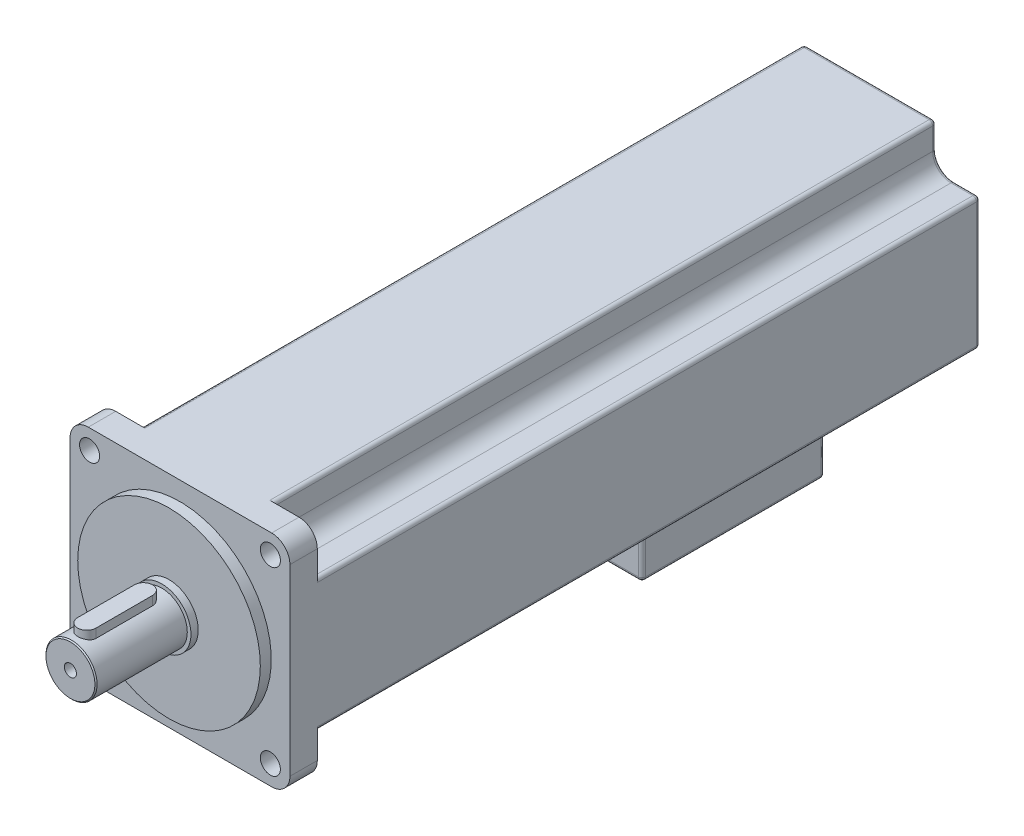
SolidWorks part; units mm, degrees
ref_plane "前视基准面" through (0, 0, 0) normal (0, 0, 1) x (1, 0, 0)
ref_plane "上视基准面" through (0, 0, 0) normal (0, 1, 0) x (1, 0, 0)
ref_plane "右视基准面" through (0, 0, 0) normal (1, 0, 0) x (0, 0, -1)
sketch "草图1" plane through (0, 0, 0) normal (0, 0, 1) x (1, 0, 0)
  line L1 (-30.1, -30.1) -> (30.1, -30.1)
  line L2 (-30.1, -30.1) -> (-30.1, 30.1)
  line L3 (-30.1, 30.1) -> (30.1, 30.1)
  line L4 (30.1, -30.1) -> (30.1, 30.1)
  line L5 (-30.1, -30.1) -> (30.1, 30.1) construction
  line L6 (-30.1, 30.1) -> (30.1, -30.1) construction
  point P0 (0, 0)
  dimension "D1" = 60.2
  dimension "D2" = 60.2
extrude "凸台-拉伸1" add sketch "草图1" along normal blind 7.5
fillet "圆角1" radius 5 4 edges at (-30.1, -30.1, 3.75) (30.1, -30.1, 3.75) (30.1, 30.1, 3.75) (-30.1, 30.1, 3.75)
sketch "草图2" plane through (0, 0, 7.5) normal (0, 0, 1) x (1, 0, 0)
  line L1 (-24.7487, 24.7487) -> (24.7487, 24.7487) construction
  line L2 (-24.7487, 24.7487) -> (-24.7487, -24.7487) construction
  line L3 (-24.7487, -24.7487) -> (24.7487, -24.7487) construction
  line L4 (24.7487, 24.7487) -> (24.7487, -24.7487) construction
  line L5 (-24.7487, 24.7487) -> (24.7487, -24.7487) construction
  line L6 (-24.7487, -24.7487) -> (24.7487, 24.7487) construction
  circle A0 centre (0, 0) radius 35 construction
  circle A1 centre (-24.7487, 24.7487) radius 2.75
  circle A2 centre (24.7487, 24.7487) radius 2.75
  circle A3 centre (24.7487, -24.7487) radius 2.75
  circle A4 centre (-24.7487, -24.7487) radius 2.75
  dimension "D1" = 70
  dimension "D2" = 5.5
extrude "切除-拉伸1" cut sketch "草图2" against normal through all
sketch "草图3" plane through (0, 0, 7.5) normal (0, 0, 1) x (1, 0, 0)
  circle A0 centre (0, 0) radius 25
  dimension "D1" = 50
extrude "凸台-拉伸2" add sketch "草图3" along normal blind 3
sketch "草图4" plane through (0, 0, 10.5) normal (0, 0, 1) x (1, 0, 0)
  circle A0 centre (0, 0) radius 8
  dimension "D1" = 16
extrude "凸台-拉伸3" add sketch "草图4" along normal blind 2
sketch "草图5" plane through (0, 0, 12.5) normal (0, 0, 1) x (1, 0, 0)
  circle A0 centre (0, 0) radius 7
  dimension "D1" = 14
extrude "凸台-拉伸4" add sketch "草图5" along normal blind 25
hole_wizard "M4 螺纹孔2" positions "草图8" profile "草图9" tap size "M4" standard "ISO"
sketch "草图8" plane through (0, 0, 37.5) normal (0, 0, 1) x (1, 0, 0)
  point P0 (0, 0)
sketch "草图9" plane through (0, 0, 37.5) normal (1, 0, 0) x (0, -1, 0)
  line L0 (0, 0) -> (0, 11.0914)
  line L1 (0, 11.0914) -> (1.65, 10.1)
  line L2 (1.65, 10.1) -> (1.65, 0)
  line L5 (1.65, 0) -> (0, 0)
  line L10 (0, 11.0914) -> (-1.65, 10.1) construction
  line L11 (0, -6.35) -> (0, 107.95) construction
  dimension "螺纹孔钻头直径" = 3.3
  dimension "螺纹孔钻头深度" = 10.1
  dimension "导头角度" = 118
cosmetic thread "孔螺蚊线2" parameters "D1"=8, "D2"=4
chamfer "倒角1" distance 0.3 angle 45 1 edges at (7, 0, 37.5)
ref_plane "基准面1" through (0, 9, 0) normal (0, 1, 0) x (1, 0, 0)
sketch "草图10" plane through (0, 9, 0) normal (0, 1, 0) x (1, 0, 0)
  line L0 (0, -33) -> (0, -17.5) construction
  line L1 (-2.5, -33) -> (-2.5, -17.5)
  line L2 (2.5, -33) -> (2.5, -17.5)
  line L3 (-6.7, -37.5) -> (6.7, -37.5) construction
  arc A0 (-2.5, -33) -> (2.5, -33) centre (0, -33) ccw
  arc A1 (2.5, -17.5) -> (-2.5, -17.5) centre (0, -17.5) ccw
  point P3 (0, -25.25)
  point P10 (0, -35.5)
  point P11 (0, -15)
  dimension "D2" = 2.5
  dimension "D1" = 20.5
  dimension "D3" = 4.5
extrude "凸台-拉伸5" add sketch "草图10" against normal blind 5
sketch "草图12" plane through (0, 0, 0) normal (0, 0, -1) x (-1, 0, 0)
  line L0 (30.1, -18.1) -> (18.1, -18.1)
  line L1 (-18.1, -30.1) -> (18.1, -30.1)
  line L2 (-30.1, -18.1) -> (-30.1, 18.1)
  line L3 (-18.1, 30.1) -> (18.1, 30.1)
  line L4 (30.1, -18.1) -> (30.1, 18.1)
  line L5 (-23.9484, -23.9484) -> (29.92, 29.92) construction
  line L6 (-30.279, 30.279) -> (30.279, -30.279) construction
  line L7 (18.1, -18.1) -> (18.1, -30.1)
  line L8 (30.1, 18.1) -> (18.1, 18.1)
  line L9 (18.1, 18.1) -> (18.1, 30.1)
  line L10 (0, 0) -> (0, -11.5891) construction
  line L11 (-18.1, 18.1) -> (-18.1, 30.1)
  line L12 (-30.1, 18.1) -> (-18.1, 18.1)
  line L13 (-18.1, -18.1) -> (-18.1, -30.1)
  line L14 (-30.1, -18.1) -> (-18.1, -18.1)
  line L15 (30.1, 25.1) -> (30.1, -25.1) construction
  line L16 (25.1, -30.1) -> (-25.1, -30.1) construction
  point P0 (0, 0)
  point P20 (30.1, -17.7072)
  point P23 (-17.1812, -30.1)
  point P26 (-7.8893, 18.1)
  dimension "D1" = 60.2
  dimension "D2" = 60.2
  dimension "D3" = 12
  dimension "D4" = 60.2
extrude "凸台-拉伸6" add sketch "草图12" along normal blind 181.5
fillet "圆角2" radius 5 4 edges at (-18.1, -18.1, -90.75) (-18.1, 18.1, -90.75) (18.1, 18.1, -90.75) (18.1, -18.1, -90.75)
sketch "草图13" plane through (0, -30.1, 0) normal (0, -1, 0) x (1, 0, 0)
  line L0 (0, -181.5) -> (0, -136.5) construction
  line L1 (18.1, -181.5) -> (-18.1, -181.5) construction
  line L3 (7.5, -111.5) -> (-7.5, -111.5)
  line L4 (7.5, -111.5) -> (7.5, -161.5)
  line L5 (7.5, -161.5) -> (-7.5, -161.5)
  line L6 (-7.5, -111.5) -> (-7.5, -161.5)
  line L7 (7.5, -111.5) -> (-7.5, -161.5) construction
  line L8 (7.5, -161.5) -> (-7.5, -111.5) construction
  dimension "D1" = 45
  dimension "D2" = 15
  dimension "D3" = 50
extrude "凸台-拉伸7" add sketch "草图13" along normal blind 20
fillet "圆角3" radius 1 32 edges at (0, -50.1, -111.5) (7.5, -50.1, -136.5) (0, -50.1, -161.5) (-7.5, -50.1, -136.5) (-26.6, -18.1, -181.5) (-19.5645, -19.5645, -181.5) (-18.1, -26.6, -181.5) (0, -30.1, -181.5) (18.1, -26.6, -181.5) (19.5645, -19.5645, -181.5) (26.6, -18.1, -181.5) (30.1, 0, -181.5) (26.6, 18.1, -181.5) (19.5645, 19.5645, -181.5) (18.1, 26.6, -181.5) (0, 30.1, -181.5) (-18.1, 26.6, -181.5) (-19.5645, 19.5645, -181.5) (-26.6, 18.1, -181.5) (-30.1, 0, -181.5) (18.1, 30.1, -90.75) (-18.1, 30.1, -90.75) (-30.1, 18.1, -90.75) (-30.1, -18.1, -90.75) (-18.1, -30.1, -90.75) (30.1, -18.1, -90.75) (30.1, 18.1, -90.75) (7.5, -40.1, -111.5) (-7.5, -40.1, -111.5) (-7.5, -40.1, -161.5) (7.5, -40.1, -161.5) (18.1, -30.1, -90.75)
